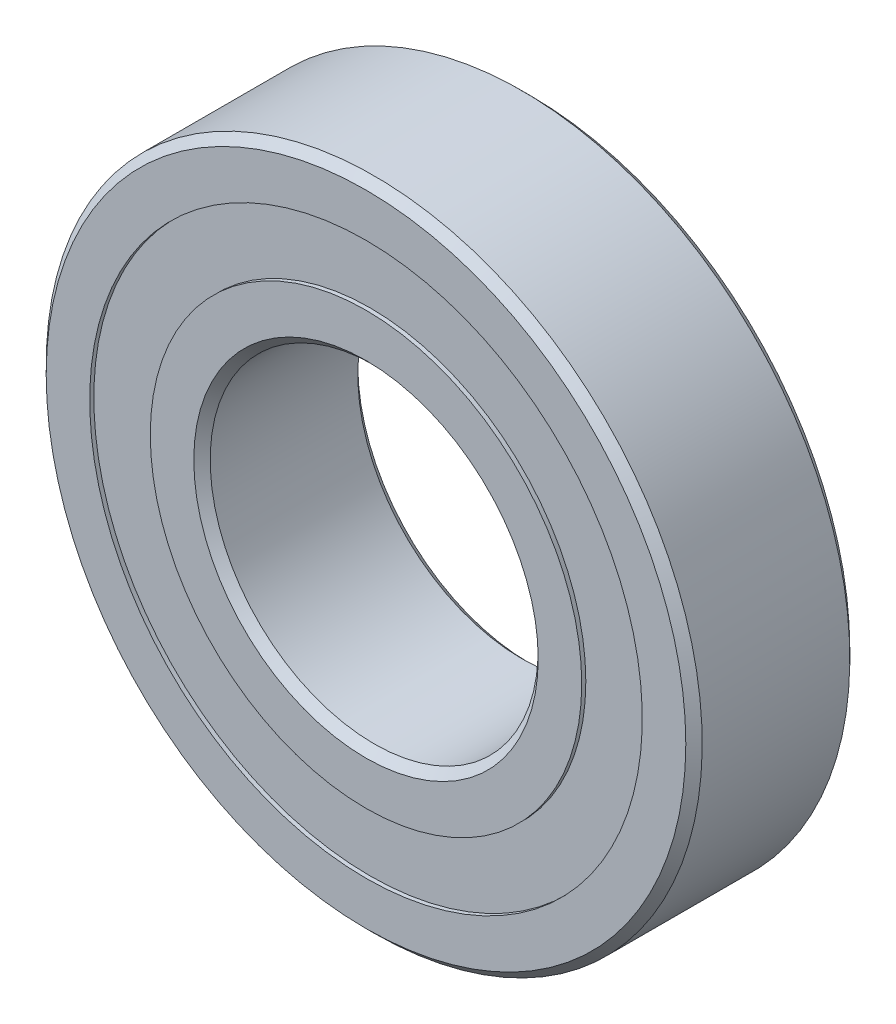
SolidWorks part; units mm, degrees
ref_plane "Front Plane" through (0, 0, 0) normal (0, 0, 1) x (1, 0, 0)
ref_plane "Top Plane" through (0, 0, 0) normal (0, 1, 0) x (1, 0, 0)
ref_plane "Right Plane" through (0, 0, 0) normal (1, 0, 0) x (0, 0, -1)
sketch "Sketch1" plane through (0, 0, 0) normal (0, 0, 1) x (1, 0, 0)
  line L0 (-25.4, 0) -> (25.4, 0) construction
  line L1 (-12.7, 0) -> (12.7, 0) construction
  circle A0 centre (0, 0) radius 12.7 construction
  circle A1 centre (0, 0) radius 25.4 construction
  point P3 (0, 0)
  point P6 (0, 0)
  point P7 (0, -12.7)
  point P11 (0, -25.4)
  point P12 (0, 12.7)
  point P13 (0, 25.4)
  dimension "OD" = 50.8
  dimension "ID" = 25.4
sketch "Sketch2" plane through (0, 0, 0) normal (1, 0, 0) x (0, 0, -1)
  line L0 (-6.35, 25.4) -> (6.35, 25.4) construction
  line L1 (0, 25.4) -> (0, -25.4) construction
  line L2 (5.715, 25.4) -> (-5.715, 25.4)
  line L3 (-5.715, 25.4) -> (-6.35, 24.765)
  line L4 (-6.35, 24.765) -> (-6.35, 21.3946)
  line L5 (-6.35, 21.3946) -> (-2.8222, 21.3946)
  line L6 (6.35, 21.3946) -> (2.8222, 21.3946)
  line L7 (6.35, 24.765) -> (6.35, 21.3946)
  line L8 (5.715, 25.4) -> (6.35, 24.765)
  line L9 (0, 25.4) -> (0, 19.05) construction
  line L10 (0, 19.05) -> (0, 12.7) construction
  line L11 (0, 25.4) -> (0, -25.4) construction
  line L12 (-6.35, 0) -> (6.35, 0) construction
  line L13 (6.35, 12.7) -> (-6.35, 12.7) construction
  line L14 (-6.35, 12.7) -> (-6.35, -12.7) construction
  line L15 (-6.35, -12.7) -> (6.35, -12.7) construction
  line L16 (6.35, 25.4) -> (6.35, -25.4) construction
  arc A0 (-2.8222, 21.3946) -> (2.8222, 21.3946) centre (0, 19.05) cw
  circle A1 centre (0, 19.05) radius 3.6691 construction
  point P14 (0, 12.7)
  point P17 (0, 0)
  point P21 (0, 25.4)
  point P29 (0, 12.7)
  point P30 (0, -12.7)
  dimension "Width" = 12.7
  dimension "D1" = 45
  dimension "D2" = 0.635
  dimension "D3" = 5.6444
  dimension "D4" = 2.3446
  dimension "For Shaft Diameter" = 25.4
  dimension "For Housing ID" = 50.8
sketch "Sketch3" plane through (0, 0, 0) normal (1, 0, 0) x (0, 0, -1)
  line L0 (5.715, 25.4) -> (6.35, 24.765) construction
  line L1 (6.35, 24.765) -> (6.35, 21.3946) construction
  line L2 (6.35, 21.3946) -> (2.8222, 21.3946) construction
  line L3 (-6.35, 21.3946) -> (-2.8222, 21.3946) construction
  line L4 (-6.35, 24.765) -> (-6.35, 21.3946) construction
  line L5 (-5.715, 25.4) -> (-6.35, 24.765) construction
  line L6 (5.715, 25.4) -> (-5.715, 25.4) construction
  line L7 (5.715, 25.4) -> (6.35, 24.765)
  line L8 (6.35, 24.765) -> (6.35, 21.3946)
  line L9 (6.35, 21.3946) -> (2.8222, 21.3946)
  line L10 (-6.35, 21.3946) -> (-2.8222, 21.3946)
  line L11 (-6.35, 24.765) -> (-6.35, 21.3946)
  line L12 (-5.715, 25.4) -> (-6.35, 24.765)
  line L13 (5.715, 25.4) -> (-5.715, 25.4)
  arc A0 (2.8222, 21.3946) -> (-2.8222, 21.3946) centre (0, 19.05) ccw construction
  arc A1 (2.8222, 21.3946) -> (-2.8222, 21.3946) centre (0, 19.05) ccw
revolve "Revolve1" add sketch "Sketch3" angle 360 about L12
sketch "Sketch4" plane through (0, 0, 0) normal (1, 0, 0) x (0, 0, -1)
  line L0 (0, 25.4) -> (0, -25.4) construction
  line L1 (0, 25.4) -> (0, -25.4) construction
  line L2 (-5.715, 12.7) -> (-6.35, 13.335)
  line L3 (-6.35, 13.335) -> (-6.35, 16.7054)
  line L5 (-6.35, 16.7054) -> (-2.8222, 16.7054)
  line L6 (-5.715, 12.7) -> (5.715, 12.7)
  line L8 (5.715, 12.7) -> (6.35, 13.335)
  line L10 (6.35, 13.335) -> (6.35, 16.7054)
  line L11 (6.35, 16.7054) -> (2.8222, 16.7054)
  line L12 (-6.35, 24.765) -> (-6.35, 21.3946) construction
  line L13 (5.715, 25.4) -> (6.35, 24.765) construction
  line L15 (6.35, -24.765) -> (6.35, 24.765) construction
  line L16 (5.715, 25.4) -> (5.715, -25.4) construction
  arc A1 (2.8222, 16.7054) -> (-2.8222, 16.7054) centre (0, 19.05) cw
  circle A2 centre (0, 19.05) radius 3.6691 construction
  point P1 (0, 12.7)
revolve "Revolve2" add sketch "Sketch4" angle 360 about L12
sketch "Sketch5" plane through (0, 0, 0) normal (1, 0, 0) x (0, 0, -1)
  line L0 (-3.6691, 19.05) -> (3.6691, 19.05)
  arc A2 (-3.6691, 19.05) -> (3.6691, 19.05) centre (0, 19.05) cw
  arc A3 (2.8222, 21.3946) -> (-2.8222, 21.3946) centre (0, 19.05) ccw construction
revolve "Revolve3" add sketch "Sketch5" angle 360 about L0
pattern_circular "CirPattern1" count 12 over 360 about axis through (0, 0, 0) along (0, 0, 1) of bodies 104
sketch "Sketch6" plane through (0, 0, 0) normal (1, 0, 0) x (0, 0, -1)
  line L0 (-6.35, 21.3946) -> (-2.8222, 21.3946) construction
  line L1 (-6.0325, 21.3946) -> (-3.6691, 21.3946)
  line L2 (-6.0325, 21.3946) -> (-6.0325, 16.7054)
  line L3 (-6.0325, 16.7054) -> (-3.6691, 16.7054)
  line L4 (-3.6691, 21.3946) -> (-3.6691, 16.7054)
  line L5 (-6.35, 16.7054) -> (-2.8222, 16.7054) construction
  line L6 (-5.715, 25.4) -> (-6.35, 24.765) construction
  line L7 (0, 25.4) -> (0, 12.7) construction
  line L8 (6.0325, 16.7054) -> (3.6691, 16.7054)
  line L9 (3.6691, 21.3946) -> (3.6691, 16.7054)
  line L10 (6.0325, 21.3946) -> (3.6691, 21.3946)
  line L11 (6.0325, 21.3946) -> (6.0325, 16.7054)
  circle A1 centre (0, 19.05) radius 3.6691 construction
  point P10 (-6.0325, 25.0825)
revolve "Revolve4" add sketch "Sketch6" angle 360 about L12
equation "\"D2@Sketch2\" = \"Width@Sketch2\" * .05"
equation "\"D3@Sketch2\" = \"Width@Sketch2\" / 2.25"
equation "\"D4@Sketch2\" =  (  (  ( \"OD@Sketch1\" - \"Width@Sketch2\" )  / 2 )  / 3.25 )  / 2.5"
